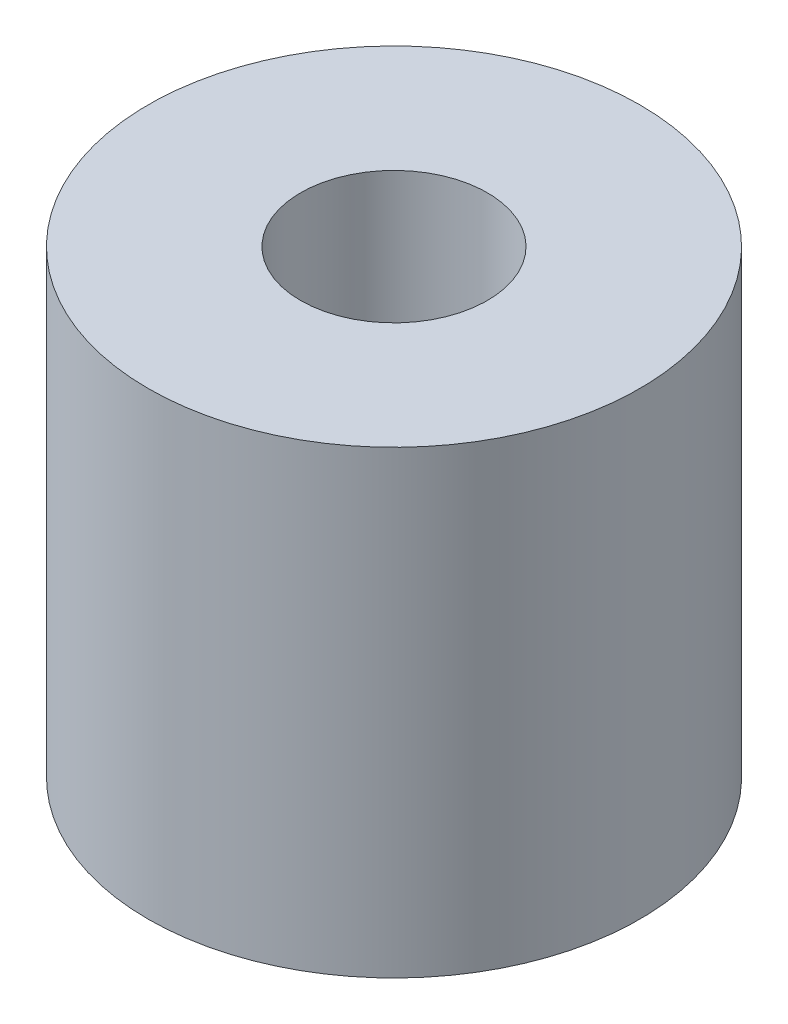
SolidWorks part; units mm, degrees
ref_plane "Front Plane" through (0, 0, 0) normal (0, 0, 1) x (1, 0, 0)
ref_plane "Top Plane" through (0, 0, 0) normal (0, 1, 0) x (1, 0, 0)
ref_plane "Right Plane" through (0, 0, 0) normal (1, 0, 0) x (0, 0, -1)
sketch "Sketch1" plane through (0, 0, 0) normal (0, 1, 0) x (1, 0, 0)
  circle A0 centre (0, 0) radius 4.8125
  dimension "D1" = 9.625
extrude "Boss-Extrude1" add sketch "Sketch1" along normal blind 9
hole_wizard "#6 Clearance Hole1" positions "Sketch2" profile "Sketch3" hole size "#6" standard "ANSI Inch" end condition through all
sketch "Sketch2" plane through (0, 9, 0) normal (0, 1, 0) x (1, 0, 0)
  point P0 (0, 0)
sketch "Sketch3" plane through (0, 9, 0) normal (1, 0, 0) x (0, 0, 1)
  line L0 (0, 0) -> (0, 9)
  line L1 (0, 9) -> (1.8288, 9)
  line L2 (1.8288, 9) -> (1.8288, 0)
  line L5 (1.8288, 0) -> (0, 0)
  line L11 (0, -6.35) -> (0, 107.95) construction
  dimension "Thru Hole Dia." = 3.6576
  dimension "Thru Hole Depth" = 9
equation "\"washer counterbore\"= 4.7625mm + 0.05mm"
equation "\"D1@Sketch1\"=2*\"washer counterbore\""
